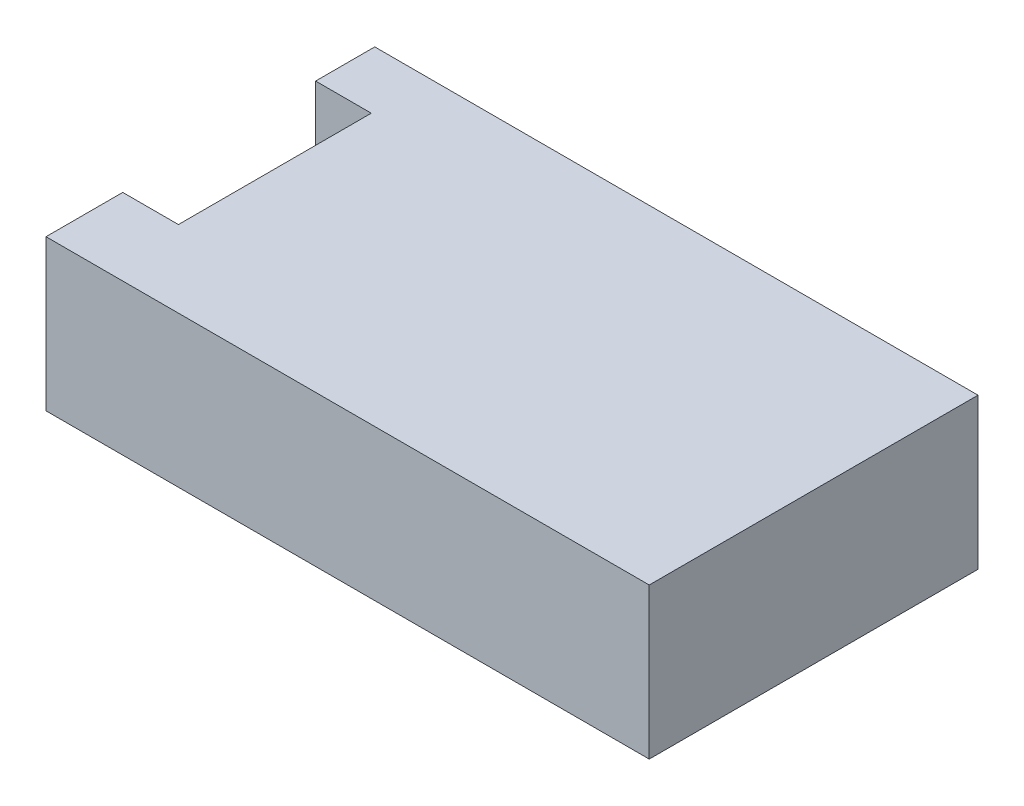
SolidWorks part; units mm, degrees
ref_plane "前视基准面" through (0, 0, 0) normal (0, 0, 1) x (1, 0, 0)
ref_plane "上视基准面" through (0, 0, 0) normal (0, 1, 0) x (1, 0, 0)
ref_plane "右视基准面" through (0, 0, 0) normal (1, 0, 0) x (0, 0, -1)
sketch "草图1" plane through (0, 0, 0) normal (0, 1, 0) x (1, 0, 0)
  line L1 (-5.412, 4.8775) -> (194.588, 4.8775)
  line L2 (-5.412, 4.8775) -> (-5.412, -104.1225)
  line L3 (-5.412, -104.1225) -> (194.588, -104.1225)
  line L4 (194.588, 4.8775) -> (194.588, -104.1225)
  line L5 (-5.412, 4.8775) -> (194.588, -104.1225) construction
  line L6 (-5.412, -104.1225) -> (194.588, 4.8775) construction
  point P4 (94.588, -49.6225)
  dimension "D1" = 200
  dimension "D2" = 109
extrude "凸台-拉伸1" add sketch "草图1" along normal blind 50
sketch "草图2" plane through (0, 50, 0) normal (0, 1, 0) x (1, 0, 0)
  line L0 (-5.412, 4.8775) -> (-5.412, -104.1225) construction
  line L1 (-5.412, -14.7345) -> (13.0487, -14.7345)
  line L2 (-5.412, -14.7345) -> (-5.412, -78.679)
  line L3 (-5.412, -78.679) -> (13.0487, -78.679)
  line L4 (13.0487, -14.7345) -> (13.0487, -78.679)
  line L5 (-5.412, -14.7345) -> (13.0487, -78.679) construction
  line L6 (-5.412, -78.679) -> (13.0487, -14.7345) construction
  point P4 (3.8183, -46.7068)
extrude "切除-拉伸1" cut sketch "草图2" against normal blind 34
sketch "草图3" plane through (0, 16, 0) normal (0, 1, 0) x (1, 0, 0)
  line L0 (-5.412, -14.7345) -> (-5.412, -78.679) construction
  line L1 (-5.412, -22.5223) -> (15.3946, -22.5223)
  line L2 (-5.412, -22.5223) -> (-5.412, -28.1607)
  line L3 (-5.412, -28.1607) -> (15.3946, -28.1607)
  line L4 (15.3946, -22.5223) -> (15.3946, -28.1607)
  line L5 (-5.412, -22.5223) -> (15.3946, -28.1607) construction
  line L6 (-5.412, -28.1607) -> (15.3946, -22.5223) construction
  point P4 (4.9913, -25.3415)
  point P7 (16.1776, -22.4211)
  point P8 (11.8677, -22.5223)
extrude "凸台-拉伸2" add sketch "草图3" along normal blind 5
pattern_linear "阵列(线性)1" count 5 spacing 10 along (0, 0, 1) of "凸台-拉伸2"
